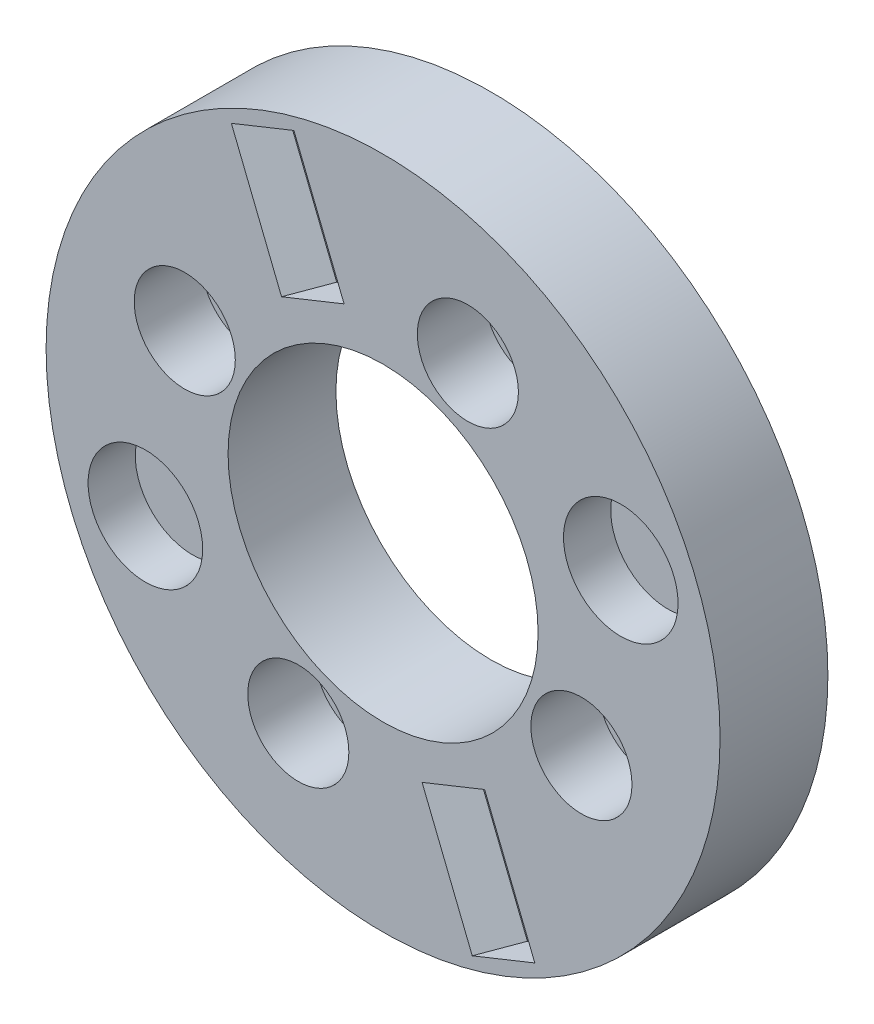
SolidWorks part; units mm, degrees
ref_plane "Plan de face" through (0, 0, 0) normal (0, 0, 1) x (1, 0, 0)
ref_plane "Plan de dessus" through (0, 0, 0) normal (0, 1, 0) x (1, 0, 0)
ref_plane "Plan de droite" through (0, 0, 0) normal (1, 0, 0) x (0, 0, -1)
sketch "Esquisse1" plane through (0, 0, 0) normal (0, 0, 1) x (1, 0, 0)
  circle A0 centre (0, 0) radius 11.5
  circle A1 centre (0, 0) radius 25
  dimension "D1" = 23
  dimension "D2" = 50
extrude "Boss.-Extru.1" add sketch "Esquisse1" along normal blind 8
sketch "Esquisse2" plane through (0, 0, 8) normal (0, 0, 1) x (1, 0, 0)
  line L0 (-14.7134, 6.2862) -> (-5.9572, 14.8496) construction
  line L1 (-5.9572, 14.8496) -> (6.2896, 14.712) construction
  line L2 (-6.2896, -14.712) -> (5.9572, -14.8496) construction
  line L3 (5.9572, -14.8496) -> (14.7134, -6.2862) construction
  line L4 (-5.9572, 14.8496) -> (0, 0) construction
  line L5 (0, 0) -> (5.9572, -14.8496) construction
  circle A0 centre (0, 0) radius 16 construction
  circle A2 centre (-14.7134, 6.2862) radius 2.5
  circle A3 centre (6.2896, 14.712) radius 2.5
  circle A4 centre (14.7134, -6.2862) radius 2.5
  circle A6 centre (-6.2896, -14.712) radius 2.5
  dimension "D1" = 32
  dimension "D3" = 5
  dimension "D2" = 22.63
extrude "Enlèv. mat.-Extru.1" cut sketch "Esquisse2" against normal through all
sketch "Esquisse4" plane through (0, 0, 8) normal (0, 0, 1) x (1, 0, 0)
  circle A0 centre (-6.2896, -14.712) radius 3.75
  circle A2 centre (14.7134, -6.2862) radius 3.75
  circle A3 centre (6.2896, 14.712) radius 3.75
  circle A5 centre (-14.7134, 6.2862) radius 3.75
  dimension "D1" = 7.5
extrude "Enlèv. mat.-Extru.2" cut sketch "Esquisse4" against normal blind 5
sketch "Esquisse5" plane through (0, 0, 8) normal (0, 0, 1) x (1, 0, 0)
  line L0 (23.2025, 9.3082) -> (0, 0) construction
  line L1 (23.2025, 9.3082) -> (14.7134, -6.2862) construction
  line L2 (14.7134, -6.2862) -> (6.2896, 14.712) construction
  line L3 (6.2896, 14.712) -> (23.2025, 9.3082) construction
  circle A2 centre (0, 0) radius 25 construction
ref_plane "Plan1" through (0, 0, 8) normal (-0.9281, -0.3723, 0) x (0, 0, 1)
ref_plane "Plan2" through (0, 0, 0) normal (-0.3723, 0.9281, 0) x (-0.9281, -0.3723, 0)
sketch "Esquisse13" plane through (0, 0, 0) normal (-0.3723, 0.9281, 0) x (-0.9281, -0.3723, 0)
  line L0 (-2.5, 8) -> (2.5, 8)
  line L1 (2.5, 8) -> (0.5, 5.7639)
  line L2 (0.5, 5.7639) -> (-0.5, 5.7639)
  line L3 (-0.5, 5.7639) -> (-2.5, 8)
  line L5 (0, -5.75) -> (0, 21.75) construction
  line L6 (-25, 8) -> (0, 8) construction
  point P5 (0, 8)
  point P12 (-12.5, 8)
  dimension "D1" = 5
  dimension "D2" = 3
  dimension "D3" = 1
extrude "Enlèv. mat.-Extru.7" cut sketch "Esquisse13" against normal blind 10 from offset 14 offset against normal yes
sketch "Esquisse14" plane through (0, 0, 5.7639) normal (0, 0, 1) x (1, 0, 0)
  line L0 (9.3999, -22.0883) -> (4.7485, -13.1796) construction
sketch "Esquisse10" plane through (0, 0, 0) normal (0, 0, -1) x (-1, 0, 0)
  line L0 (-9.3999, -22.0883) -> (-4.7485, -13.1796) construction
  line L4 (7.0742, 17.6339) -> (17.6339, -7.0742) construction
  line L5 (17.6339, -7.0742) -> (-7.0742, -17.6339) construction
  line L6 (-7.0742, -17.6339) -> (-17.6339, 7.0742) construction
  line L7 (-17.6339, 7.0742) -> (7.0742, 17.6339) construction
  line L8 (7.0742, 17.6339) -> (-7.0742, -17.6339) construction
  circle A0 centre (7.0742, 17.6339) radius 4.25
  circle A2 centre (-7.0742, -17.6339) radius 4.25
  point P7 (-17.6339, 7.0742)
  point P8 (0, 0)
  point P9 (17.6339, -7.0742)
extrude "Enlèv. mat.-Extru.5" cut sketch "Esquisse10" against normal blind 3.5
sketch "Esquisse12" plane through (0, 0, 8) normal (0, 0, 1) x (1, 0, 0)
  line L0 (17.6339, 7.0742) -> (7.0742, -17.6339) construction
  line L1 (7.0742, -17.6339) -> (-17.6339, -7.0742) construction
  line L2 (-17.6339, -7.0742) -> (-7.0742, 17.6339) construction
  line L3 (-7.0742, 17.6339) -> (17.6339, 7.0742) construction
  line L5 (17.6339, 7.0742) -> (-17.6339, -7.0742) construction
  line L6 (9.3999, -22.0883) -> (4.7485, -13.1796) construction
  circle A0 centre (17.6339, 7.0742) radius 4.25
  circle A1 centre (-17.6339, -7.0742) radius 4.25
  point P2 (0, 0)
  dimension "D1" = 8.5
extrude "Enlèv. mat.-Extru.6" cut sketch "Esquisse12" against normal blind 3.5
mirror "Symétrie1" about plane through (0, 0, 0) normal (-0.3723, 0.9281, 0) of "Enlèv. mat.-Extru.7"
